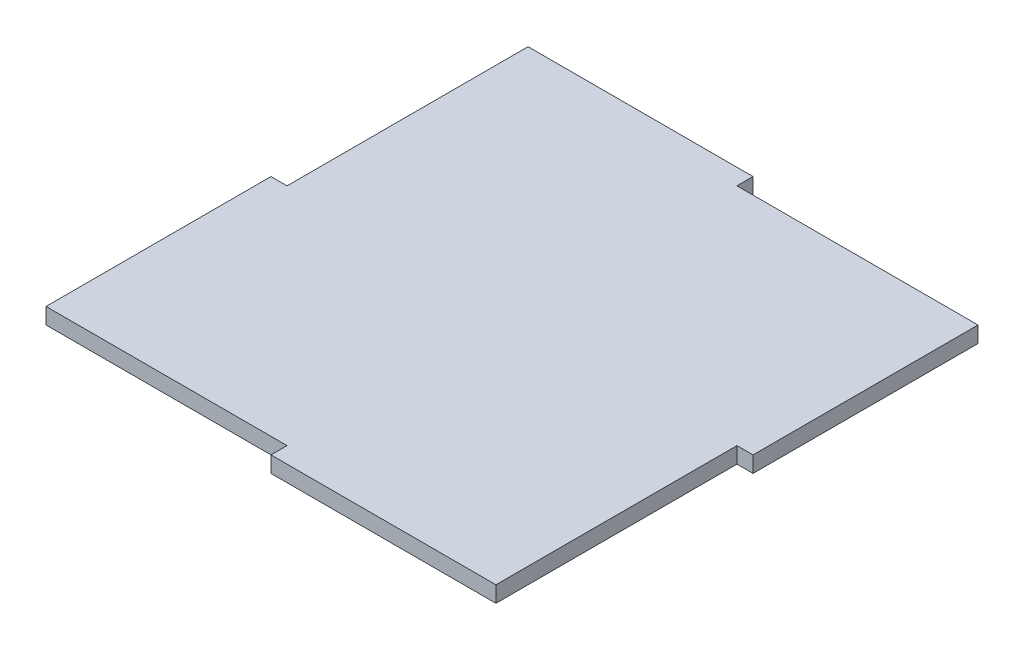
SolidWorks part; units mm, degrees
material "Acrylic (Medium-high impact)"
ref_plane "Front Plane" through (0, 0, 0) normal (0, 0, 1) x (1, 0, 0)
ref_plane "Top Plane" through (0, 0, 0) normal (0, 1, 0) x (1, 0, 0)
ref_plane "Right Plane" through (0, 0, 0) normal (1, 0, 0) x (0, 0, -1)
sketch "Sketch1" plane through (0, 0, 0) normal (0, 1, 0) x (1, 0, 0)
  line L0 (-112.5062, 93.3127) -> (-112.5062, 99.6627)
  line L1 (-112.5062, 93.3127) -> (65.2938, 93.3127)
  line L2 (-112.5062, 93.3127) -> (-112.5062, -84.4873)
  line L3 (-112.5062, -84.4873) -> (65.2938, -84.4873)
  line L4 (65.2938, 93.3127) -> (65.2938, -84.4873)
  line L5 (-112.5062, 99.6627) -> (-23.6062, 99.6627)
  line L6 (-23.6062, 99.6627) -> (-23.6062, 93.3127)
  line L7 (-112.5062, -84.4873) -> (-118.8562, -84.4873)
  line L8 (-118.8562, -84.4873) -> (-118.8562, 4.4127)
  line L9 (-118.8562, 4.4127) -> (-112.5062, 4.4127)
  line L10 (65.2938, -84.4873) -> (65.2938, -90.8373)
  line L11 (65.2938, -90.8373) -> (-23.6062, -90.8373)
  line L12 (-23.6062, -90.8373) -> (-23.6062, -84.4873)
  line L13 (65.2938, 93.3127) -> (71.6438, 93.3127)
  line L14 (71.6438, 93.3127) -> (71.6438, 4.4127)
  line L15 (71.6438, 4.4127) -> (65.2938, 4.4127)
  point P4 (-23.6062, 93.3127)
  point P5 (-112.5062, 4.4127)
  point P9 (65.2938, 4.4127)
  point P10 (-23.6062, -84.4873)
  dimension "D1" = 177.8
  dimension "D2" = 177.8
  dimension "D3" = 6.35
  dimension "D4" = 6.35
  dimension "D5" = 6.35
  dimension "D6" = 6.35
extrude "Boss-Extrude1" add sketch "Sketch1" along normal blind 6.35 contours L9 L8 L7 L2 | L6 L5 L0 L1 | L4 L1 L2 L3 | L15 L14 L13 L4 | L12 L11 L10 L3
